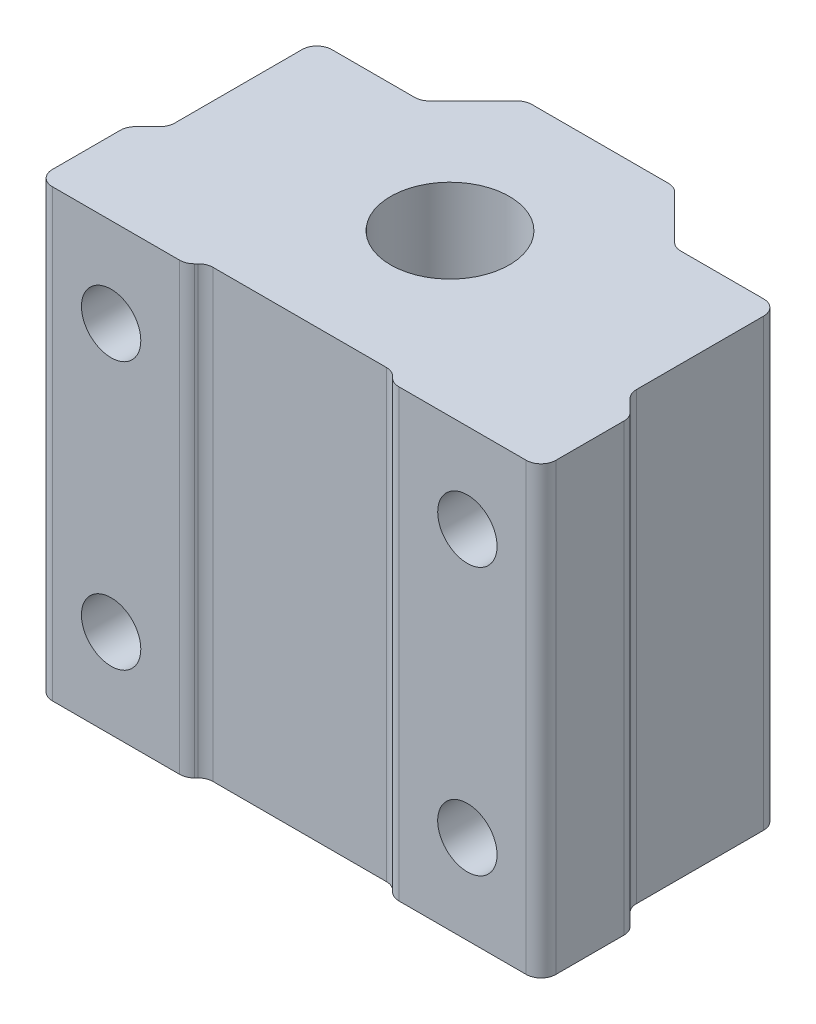
SolidWorks part; units mm, degrees
ref_plane "前视基准面" through (0, 0, 0) normal (0, 0, 1) x (1, 0, 0)
ref_plane "上视基准面" through (0, 0, 0) normal (0, 1, 0) x (1, 0, 0)
ref_plane "右视基准面" through (0, 0, 0) normal (1, 0, 0) x (0, 0, -1)
sketch "草图1" plane through (0, 0, 0) normal (0, 1, 0) x (1, 0, 0)
  line L0 (-40.5668, 0.4142) -> (-31.981, 0.4142)
  line L1 (-31.2739, 0.7071) -> (-31.1525, 0.8284)
  line L2 (-41.5668, 1.4142) -> (-41.5668, 6)
  line L3 (-41.2739, 6.7071) -> (-40.4454, 7.5355)
  line L4 (-40.1525, 8.2426) -> (-40.1525, 16.8284)
  line L5 (-39.1525, 17.8284) -> (-33.5668, 17.8284)
  line L6 (-32.8596, 18.1213) -> (-29.9099, 21.0711)
  line L7 (-29.2028, 21.364) -> (-20.0045, 21.364)
  line L8 (-30.4454, 1.1213) -> (-18.7618, 1.1213)
  line L10 (-16.3476, 18.1213) -> (-19.2974, 21.0711)
  line L11 (-10.0547, 17.8284) -> (-15.6405, 17.8284)
  line L12 (-9.0547, 8.2426) -> (-9.0547, 16.8284)
  line L13 (-7.9334, 6.7071) -> (-8.7618, 7.5355)
  line L14 (-7.6405, 1.4142) -> (-7.6405, 6)
  line L15 (-17.9334, 0.7071) -> (-18.0547, 0.8284)
  line L16 (-8.6405, 0.4142) -> (-17.2263, 0.4142)
  arc A0 (-31.1525, 0.8284) -> (-30.4454, 1.1213) centre (-30.4454, 0.1213) cw
  arc A1 (-31.981, 0.4142) -> (-31.2739, 0.7071) centre (-31.981, 1.4142) ccw
  arc A2 (-40.5668, 0.4142) -> (-41.5668, 1.4142) centre (-40.5668, 1.4142) cw
  arc A3 (-41.5668, 6) -> (-41.2739, 6.7071) centre (-40.5668, 6) cw
  arc A4 (-40.4454, 7.5355) -> (-40.1525, 8.2426) centre (-41.1525, 8.2426) ccw
  arc A5 (-40.1525, 16.8284) -> (-39.1525, 17.8284) centre (-39.1525, 16.8284) cw
  arc A6 (-33.5668, 17.8284) -> (-32.8596, 18.1213) centre (-33.5668, 18.8284) ccw
  arc A7 (-29.9099, 21.0711) -> (-29.2028, 21.364) centre (-29.2028, 20.364) cw
  arc A8 (-19.2974, 21.0711) -> (-20.0045, 21.364) centre (-20.0045, 20.364) ccw
  arc A9 (-15.6405, 17.8284) -> (-16.3476, 18.1213) centre (-15.6405, 18.8284) cw
  arc A10 (-9.0547, 16.8284) -> (-10.0547, 17.8284) centre (-10.0547, 16.8284) ccw
  arc A11 (-8.7618, 7.5355) -> (-9.0547, 8.2426) centre (-8.0547, 8.2426) cw
  arc A12 (-7.6405, 6) -> (-7.9334, 6.7071) centre (-8.6405, 6) ccw
  arc A13 (-8.6405, 0.4142) -> (-7.6405, 1.4142) centre (-8.6405, 1.4142) ccw
  arc A14 (-17.2263, 0.4142) -> (-17.9334, 0.7071) centre (-17.2263, 1.4142) cw
  arc A15 (-18.0547, 0.8284) -> (-18.7618, 1.1213) centre (-18.7618, 0.1213) ccw
  circle A16 centre (-24.6036, 11.2426) radius 4
  point P35 (-24.6036, 1.1213)
  dimension "D1" = 1
extrude "凸台-拉伸1" add sketch "草图1" along normal blind 30
sketch "草图3" plane through (0, 0, -0.4142) normal (0, 0, 1) x (1, 0, 0)
  line L0 (-8.6405, 15) -> (-40.5668, 15) construction
  line L1 (-8.6405, 30) -> (-8.6405, 0) construction
  line L2 (-40.5668, 30) -> (-40.5668, 0) construction
  line L5 (-24.6036, 15) -> (-24.6036, 48.6029) construction
  circle A0 centre (-12.6036, 6) radius 2
  circle A1 centre (-36.6036, 6) radius 2
  circle A2 centre (-36.6036, 24) radius 2
  circle A3 centre (-12.6036, 24) radius 2
  dimension "D3" = 4
  dimension "D1" = 18
  dimension "D2" = 24
  dimension "D4" = 12
  dimension "D5" = 9
  dimension "D6" = 12
  dimension "D7" = 9
  dimension "D8" = 18
  dimension "D9" = 12
extrude "切除-拉伸1" cut sketch "草图3" against normal blind 100
